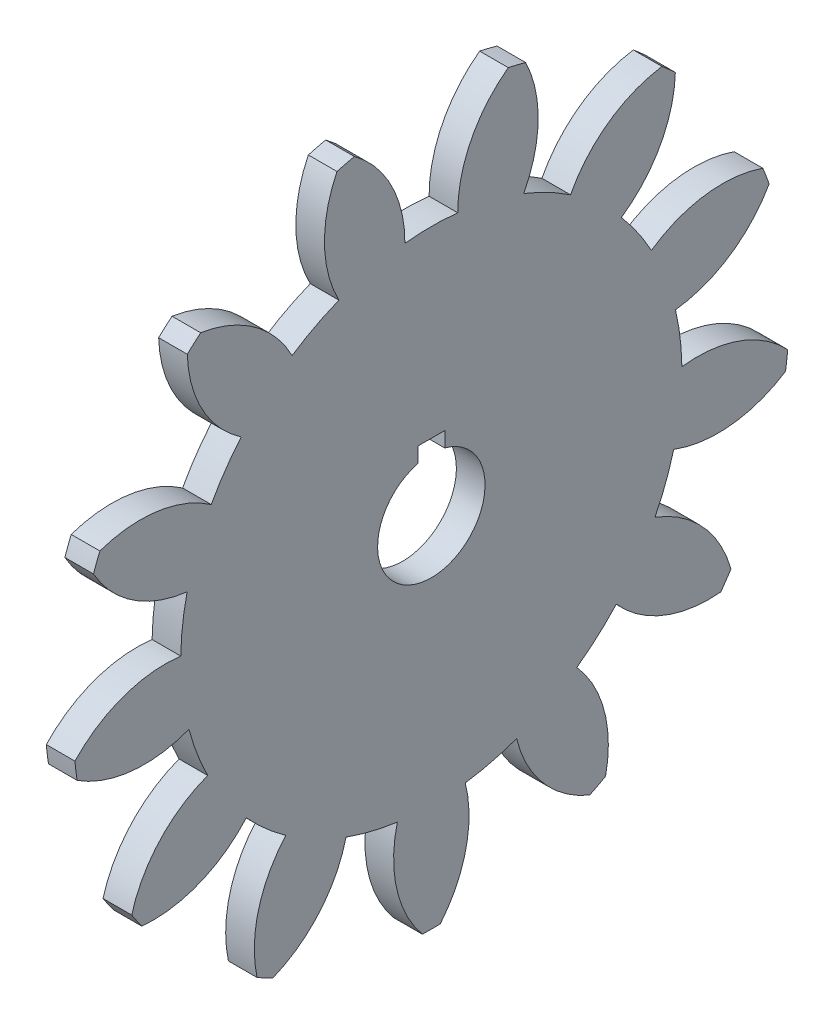
SolidWorks part; units mm, degrees
ref_plane "Plane1" through (0, 0, 0) normal (0, 0, 1) x (1, 0, 0)
ref_plane "Plane2" through (0, 0, 0) normal (0, 1, 0) x (1, 0, 0)
ref_plane "Plane3" through (0, 0, 0) normal (1, 0, 0) x (0, 0, -1)
sketch "HoldingSke" plane through (0, 0, 0) normal (0, 1, 0) x (1, 0, 0)
  line L0 (0, 0) -> (148.494, -34.2825)
  line L1 (-15, 0) -> (100, 0) construction
  line L2 (0, 0) -> (-2.1039, 2.3779)
  line L3 (0, 0) -> (-11.863, 4.5341)
  line L4 (0, 0) -> (8.4147, 1.9427)
  line L5 (0, 0) -> (-47.5972, -17.7524)
  line L6 (0, 0) -> (-2.1056, -1.4206)
  line L7 (-2.1039, 2.3779) -> (8.8308, 51.9871)
  line L8 (-76.2, 54.61) -> (-65.4837, 54.61)
  line L9 (-71.009, 38.7566) -> (-53.1078, 45.2721)
  line L10 (-76.2, 71.12) -> (104.1128, 71.12)
  line L11 (0, 0) -> (-2.54, 0)
  line L12 (-76.2, 101.6) -> (-76.0298, 101.6)
  line L13 (24.9733, 27.94) -> (52.9518, 28.4284)
  line L14 (24.9733, 27.94) -> (24.9746, 27.94)
  line L15 (24.9733, 27.94) -> (100.4006, 29.5858)
  circle A0 centre (0, 0) radius 4.7625
  circle A1 centre (0, 0) radius 22.2237
  circle A2 centre (0, 0) radius 38.1
  circle A3 centre (0, 0) radius 4.7625
  dimension "MHD" = 44.4475
  dimension "Hub_dia" = 76.2
  dimension "Bore" = 9.525
  dimension "MBD" = 9.525
  dimension "Num_teeth" = 13
  dimension "Pitch" = 152.4
  dimension "Overall_len" = 50.8
  dimension "Show_teeth" = 13
  dimension "Thickness" = 2.54
  dimension "OAL" = 50.8001
  dimension "T_dim" = 10.7163
  dimension "Ap" = 20
  dimension "H" = 19.05
  dimension "Pitch_radius" = 180.3128
  dimension "Width" = 2.54
  dimension "Backlash" = 0.1702
  dimension "Addendum_fac" = 1
  dimension "Dedendum_fac" = 1.25
  dimension "Clearance_fac" = 0.25
  dimension "Dedendum_add" = 0.0013
sketch "BasProSke" plane through (0, 0, 0) normal (0, 1, 0) x (1, 0, 0)
  line L0 (-10, 0) -> (60, 0) construction
  line L1 (0, 0) -> (0, 31.75)
  line L2 (0, 0) -> (2.54, 0)
  line L3 (2.54, 0) -> (2.54, 31.75)
  line L4 (2.54, 31.75) -> (0, 31.75)
  dimension "Thickness" = 2.54
  dimension "Diameter" = 63.5
revolve "Base-Revolve" add sketch "BasProSke" angle 360 about L0
sketch "TooCutSke" plane through (0, 0, 0) normal (1, 0, 0) x (0, 0, -1)
  line L1 (0, 0) -> (0, 107) construction
  line L2 (0, 0) -> (-3.6142, 27.2783) construction
  line L3 (0, 0) -> (-13.0908, 53.1116) construction
  line L4 (-3.6142, 27.2783) -> (-6.5454, 26.5558) construction
  arc A0 (2.3436, 22.0998) -> (-2.3436, 22.0998) centre (0, 0) ccw
  arc A1 (6.8518, 31.0279) -> (-6.8518, 31.0279) centre (0, 0) ccw
  circle A2 centre (0, 0) radius 27.5167 construction
  circle A3 centre (0, 0) radius 25.8572 construction
  arc A4 (-2.3436, 22.0998) -> (-6.8518, 31.0279) centre (-13.3501, 22.1443) ccw
  arc A5 (6.8518, 31.0279) -> (2.3436, 22.0998) centre (13.3501, 22.1443) ccw
  dimension "Root_dia" = 44.4475
  dimension "Overcut_dia" = 63.5508
  dimension "Pitch_dia" = 55.0333
  dimension "Base_dia" = 51.7144
  dimension "Flank_rad" = 11.0067
  dimension "Half_ang" = 13.846
  dimension "Half_CT" = 3.019
extrude "ToothCut" cut sketch "TooCutSke" along normal through all
fillet "Breaks" [suppressed] radius 0.0847
fillet "RootFillets" [suppressed] radius 1.0596
pattern_circular "TeethCuts" count 13 every 27.692 about axis through (-10, 0, 0) along (1, 0, 0) of "ToothCut", "RootFillets", "Breaks"
sketch "HubNeaOneSke" plane through (0, 0, 0) normal (-1, 0, 0) x (0, 0, 1)
  circle A0 centre (0, 0) radius 22.2237
  dimension "Diameter" = 44.4475
extrude "HubNearOne" [suppressed] add sketch "HubNeaOneSke" along normal blind 48.2601
sketch "HubNeaBotSke" plane through (0, 0, 0) normal (-1, 0, 0) x (0, 0, 1)
  circle A0 centre (0, 0) radius 22.2237
  dimension "Diameter" = 44.4475
extrude "HubNearBoth" [suppressed] add sketch "HubNeaBotSke" along normal blind 24.13
ref_plane "FarPln" through (2.54, 0, 0) normal (1, 0, 0) x (0, 0, -1)
sketch "HubFarSke" plane through (2.54, 0, 0) normal (1, 0, 0) x (0, 0, -1)
  circle A0 centre (0, 0) radius 22.2237
  dimension "Diameter" = 44.4475
extrude "HubFar" [suppressed] add sketch "HubFarSke" along normal blind 24.13
sketch "BorSke" plane through (0, 0, 0) normal (1, 0, 0) x (0, 0, -1)
  circle A0 centre (0, 0) radius 4.7625
  dimension "Diameter" = 9.525
extrude "Bore" cut sketch "BorSke" along normal mid plane 101.6001
sketch "KeySke" plane through (0, 0, 0) normal (1, 0, 0) x (0, 0, -1)
  line L0 (-1.1913, 0) -> (-1.1913, 5.9538)
  line L1 (-1.1913, 5.9538) -> (1.1913, 5.9538)
  line L2 (1.1913, 5.9538) -> (1.1913, 0)
  line L3 (0, 0) -> (0, 34) construction
  line L4 (-1.1913, 0) -> (1.1913, 0)
  dimension "Offset" = 5.9538
  dimension "Width" = 2.3825
extrude "Keyway" cut sketch "KeySke" along normal mid plane 101.6001
pattern_circular "Keyway2" [suppressed] count 2 every 90 about axis through (-10, 0, 0) along (1, 0, 0)
equation "' \"Pitch@HoldingSke\" = 4"
equation "' \"Num_teeth@HoldingSke\" = 12"
equation "' \"Ap@HoldingSke\" =  20"
equation "' \"Ap@HoldingSke\" = 20"
equation "' \"Width@HoldingSke\" = 0.5"
equation "' \"Hub_dia@HoldingSke\"= 1"
equation "' \"Hub_dia@HoldingSke\" = 1"
equation "' \"Overall_len@HoldingSke\" = 1.0"
equation "' \"Bore@HoldingSke\" = 0.75"
equation "' \"T_dim@HoldingSke\" = 0.85"
equation "' \"Width@KeySke\" = 0.25"
equation "' \"Show_teeth@HoldingSke\" = 13"
equation "' \"Backlash@HoldingSke\" = 0.009"
equation "' \"Addendum_fac@HoldingSke\" = 1.0"
equation "' \"Dedendum_fac@HoldingSke\" = 1.25"
equation "' \"Dedendum_add@HoldingSke\" = 0.00005"
equation "' \"Clearance_fac@HoldingSke\" = 0.25"
equation "' \"Pitch@HoldingSke\" = 0.5"
equation "' \"Num_teeth@HoldingSke\" = 23"
equation "' \"Show_teeth@HoldingSke\" = 23"
equation "' \"Backlash@HoldingSke\" = 0.0375"
equation "\"Overcut_dia@TooCutSke\" = (\"Num_teeth@HoldingSke\" + 2 * \"Addendum_fac@HoldingSke\") / \"Pitch@HoldingSke\" + 0.002"
equation "\"Pitch_dia@TooCutSke\" = \"Num_teeth@HoldingSke\" / \"Pitch@HoldingSke\""
equation "\"Base_dia@TooCutSke\" = \"Num_teeth@HoldingSke\" / \"Pitch@HoldingSke\" * cos((\"Ap@HoldingSke\"  * 3.14159265 / 180))"
equation "\"Root_dia@TooCutSke\" = (\"Num_teeth@HoldingSke\" + 2) / \"Pitch@HoldingSke\" - 2 * (\"Addendum_fac@HoldingSke\" + \"Dedendum_fac@HoldingSke\") / \"Pitch@HoldingSke\" - \"Dedendum_add@HoldingSke\" * 2"
equation "\"Half_ang@TooCutSke\" = 180 / \"Num_teeth@HoldingSke\""
equation "\"Half_CT@TooCutSke\" = \"Num_teeth@HoldingSke\" / \"Pitch@HoldingSke\" * sin((3.14159265 / 2 / \"Num_teeth@HoldingSke\")) / 2 - 7 * \"Backlash@HoldingSke\" / 4"
equation "\"Flank_rad@TooCutSke\" = \"Num_teeth@HoldingSke\" / \"Pitch@HoldingSke\" / 5"
equation "\"Radius@RootFillets\" = \"Clearance_fac@HoldingSke\" / \"Pitch@HoldingSke\" + \"Dedendum_add@HoldingSke\""
equation "\"Break_rad@Breaks\" = 0.02 / \"Pitch@HoldingSke\""
equation "\"Thickness@HoldingSke\" = \"Width@HoldingSke\""
equation "\"OAL@HoldingSke\" = \"Thickness@HoldingSke\""
equation "\"MHD@HoldingSke\" = (\"Num_teeth@HoldingSke\" + 2) / \"Pitch@HoldingSke\" - 2 * (\"Addendum_fac@HoldingSke\" + \"Dedendum_fac@HoldingSke\")  / \"Pitch@HoldingSke\" - \"Dedendum_add@HoldingSke\" * 2"
equation "\"MBD@HoldingSke\" = (\"Num_teeth@HoldingSke\" + 2) / \"Pitch@HoldingSke\" - 2 * (\"Addendum_fac@HoldingSke\" + \"Dedendum_fac@HoldingSke\")  / \"Pitch@HoldingSke\" - \"Dedendum_add@HoldingSke\" * 2 - 0.002"
equation "\"MHD@HoldingSke\" = ((sgn( \"MHD@HoldingSke\" - \"Hub_dia@HoldingSke\" )-1)*( \"MHD@HoldingSke\" - \"Hub_dia@HoldingSke\" ))/-2+ \"Hub_dia@HoldingSke\""
equation "\"MBD@HoldingSke\" = ((sgn( \"MBD@HoldingSke\" - \"Bore@HoldingSke\" )-1)*( \"MBD@HoldingSke\" - \"Bore@HoldingSke\" ))/-2+ \"Bore@HoldingSke\""
equation "\"OAL@HoldingSke\" = ((sgn( \"OAL@HoldingSke\" - \"Overall_len@HoldingSke\" )+1)*( \"OAL@HoldingSke\" - \"Overall_len@HoldingSke\" ))/2 + \"Overall_len@HoldingSke\" + 0.000002"
equation "\"Num_teeth@TeethCuts\" = int( \"Show_teeth@HoldingSke\" ) + 1"
equation "\"Num_teeth@TeethCuts\" = ((sgn( \"Num_teeth@TeethCuts\" - \"Num_teeth@HoldingSke\" )-1)*( \"Num_teeth@TeethCuts\" - \"Num_teeth@HoldingSke\" ))/-2+ \"Num_teeth@HoldingSke\""
equation "\"Num_teeth@TeethCuts\" = ((sgn( \"Num_teeth@TeethCuts\" - 2.0)+1)*( \"Num_teeth@TeethCuts\" - 2.0))/2 +2.0"
equation "\"Angle@TeethCuts\" = 360.0 / \"Num_teeth@HoldingSke\""
equation "\"Diameter@BasProSke\" = (\"Num_teeth@HoldingSke\" + 2 * \"Addendum_fac@HoldingSke\") / \"Pitch@HoldingSke\""
equation "\"Thickness@BasProSke\"  = \"Thickness@HoldingSke\""
equation "' \"Fillet_rad@BasProSke\" =  \"Thickness@HoldingSke\" * 0.05"
equation "' \"Fillet_rad@BasProSke\" = \"Thickness@HoldingSke\" * 0.05"
equation "\"MHD@HoldingSke\" = ((sgn( \"MHD@HoldingSke\" - \"Root_dia@TooCutSke\" )-1)*( \"MHD@HoldingSke\" - \"Root_dia@TooCutSke\" ))/-2+ \"Root_dia@TooCutSke\""
equation "\"Diameter@HubNeaOneSke\" = \"MHD@HoldingSke\""
equation "\"Length@HubNearOne\" = \"OAL@HoldingSke\" - \"Thickness@BasProSke\""
equation "\"Diameter@HubNeaBotSke\" = \"MHD@HoldingSke\""
equation "\"Length@HubNearBoth\" = ( \"OAL@HoldingSke\" - \"Thickness@BasProSke\" ) / 2.0"
equation "\"Thickness@FarPln\" = \"Thickness@BasProSke\""
equation "\"Diameter@HubFarSke\" = \"MHD@HoldingSke\""
equation "\"Length@HubFar\" = ( \"OAL@HoldingSke\" - \"Thickness@BasProSke\" ) / 2.0"
equation "\"Diameter@BorSke\" = \"MBD@HoldingSke\""
equation "\"D1@Bore\" = \"OAL@HoldingSke\" * 2.0"
equation "\"D1@Keyway\" = \"OAL@HoldingSke\" * 2.0"
equation "\"Offset@KeySke\" = \"T_dim@HoldingSke\" - \"MBD@HoldingSke\" / 2.0"
